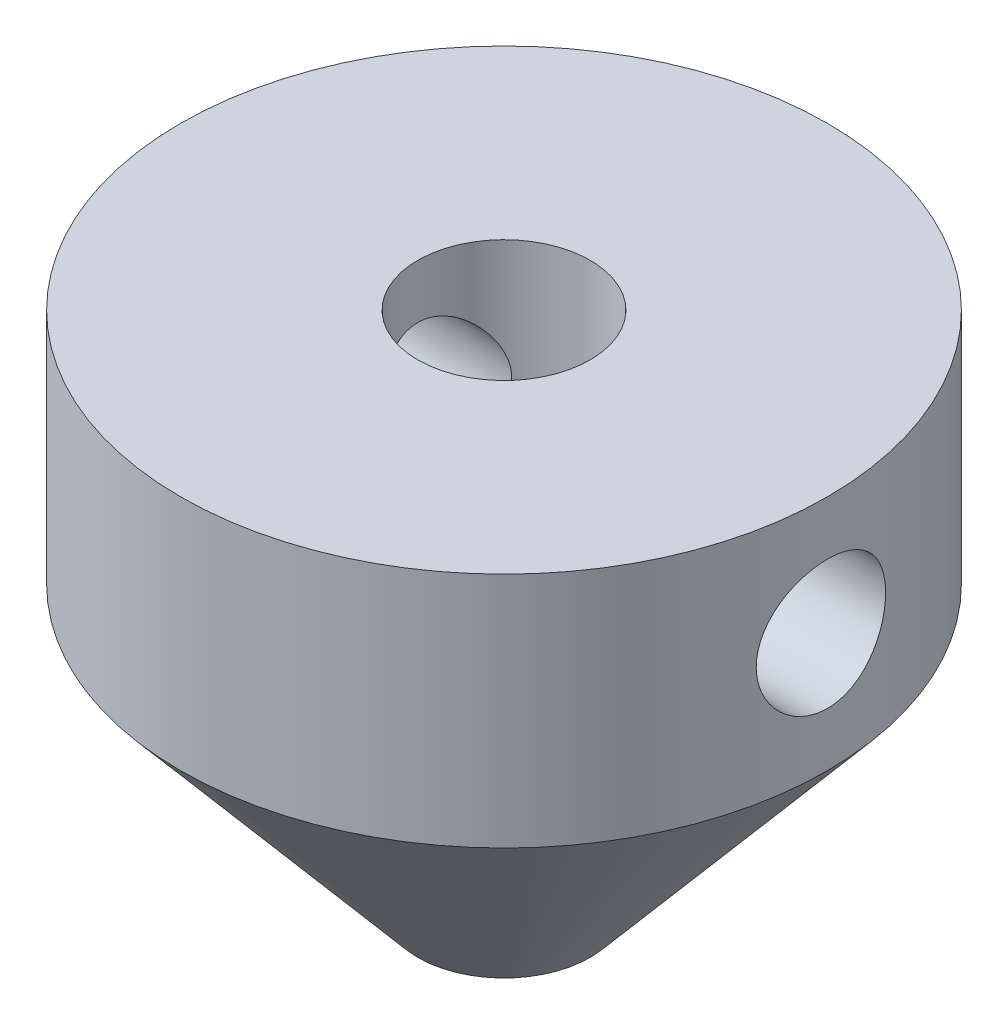
SolidWorks part; units mm, degrees
ref_plane "Front Plane" through (0, 0, 0) normal (0, 0, 1) x (1, 0, 0)
ref_plane "Top Plane" through (0, 0, 0) normal (0, 1, 0) x (1, 0, 0)
ref_plane "Right Plane" through (0, 0, 0) normal (1, 0, 0) x (0, 0, -1)
sketch "Sketch1" plane through (0, 0, 0) normal (1, 0, 0) x (0, 0, -1)
  line L0 (0, 0) -> (-7.5, 0)
  line L1 (-7.5, 0) -> (-7.5, -5.5)
  line L4 (0, -12) -> (0, 0)
  line L5 (-7.5, -5.5) -> (-2, -12)
  line L6 (-2, -12) -> (0, -12)
  dimension "D1" = 5.5
  dimension "D2" = 12
  dimension "D3" = 7.5
  dimension "D4" = 2
revolve "Revolve1" add sketch "Sketch1" angle 360 about L4
sketch "Sketch2" plane through (0, 0, 0) normal (1, 0, 0) x (0, 0, -1)
  line L1 (7.5, 0) -> (-7.5, 0) construction
  circle A0 centre (0, -2.75) radius 1.5
  dimension "D1" = 3
  dimension "D2" = 2.75
extrude "Cut-Extrude1" cut sketch "Sketch2" against normal through all both and the other way through all
sketch "Sketch3" plane through (0, 0, 0) normal (0, 1, 0) x (1, 0, 0)
  circle A0 centre (0, 0) radius 2
  dimension "D1" = 4
extrude "Cut-Extrude2" cut sketch "Sketch3" against normal through all
ref_plane "Plane1" through (0, -12, 0) normal (0, 1, 0) x (1, 0, 0)
sketch "Sketch5" plane through (0, -12, 0) normal (0, 1, 0) x (1, 0, 0)
  circle A0 centre (0, 0) radius 3
  point P3 (0, 0)
  dimension "D1" = 6
